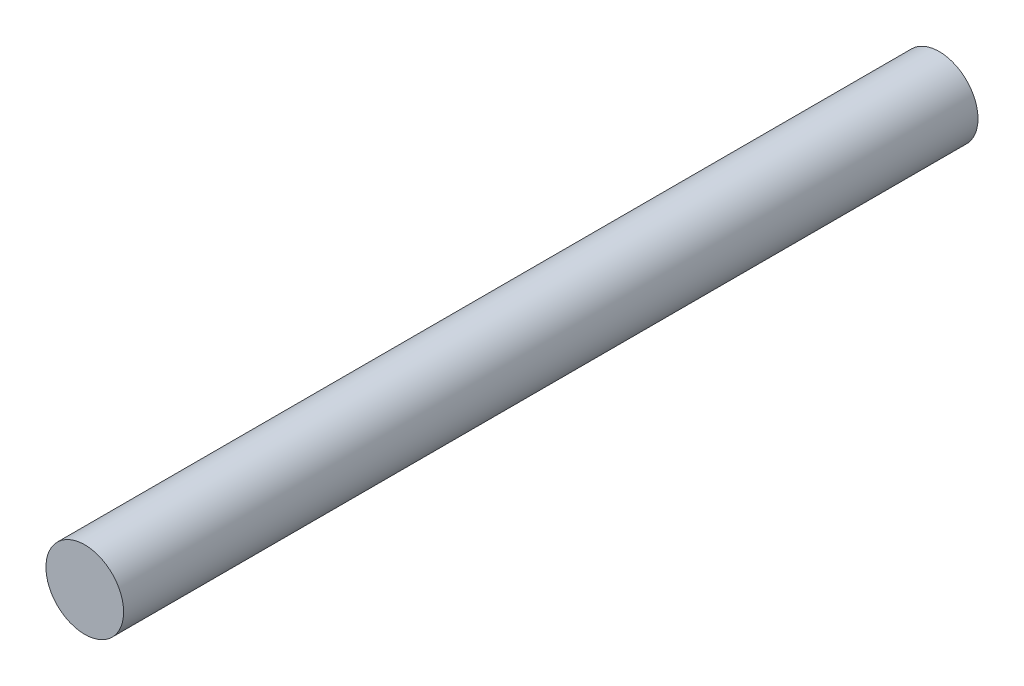
SolidWorks part; units mm, degrees
ref_plane "Front Plane" through (0, 0, 0) normal (0, 0, 1) x (1, 0, 0)
ref_plane "Top Plane" through (0, 0, 0) normal (0, 1, 0) x (1, 0, 0)
ref_plane "Right Plane" through (0, 0, 0) normal (1, 0, 0) x (0, 0, -1)
sketch "Sketch1" plane through (0, 0, 0) normal (0, 0, 1) x (1, 0, 0)
  circle A0 centre (0, 0) radius 5
  dimension "D1" = 10
extrude "Boss-Extrude1" add sketch "Sketch1" along normal blind 110
